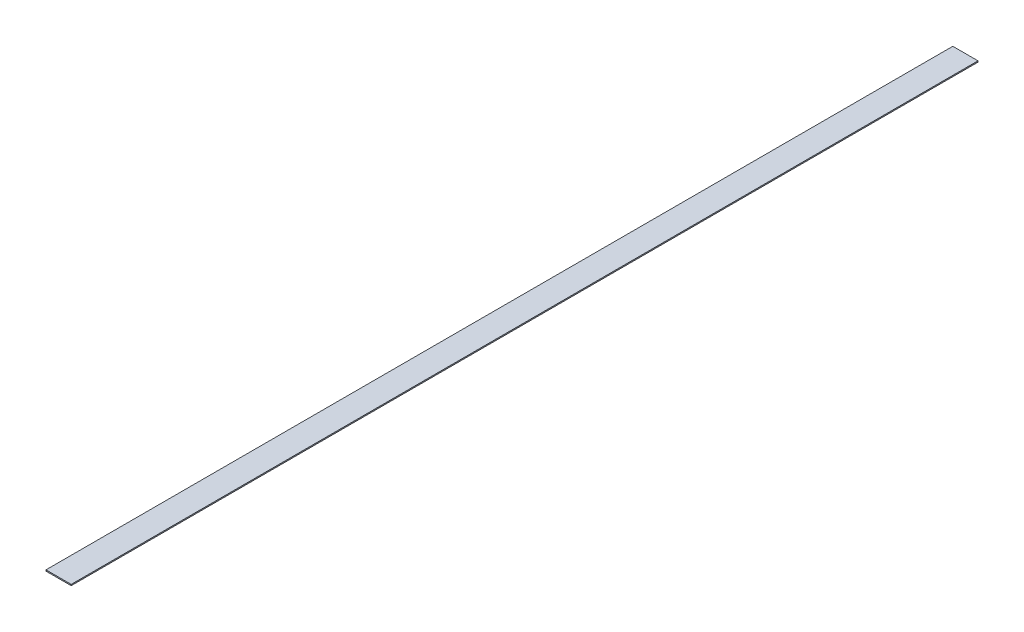
SolidWorks part; units mm, degrees
ref_plane "Front Plane" through (0, 0, 0) normal (0, 0, 1) x (1, 0, 0)
ref_plane "Top Plane" through (0, 0, 0) normal (0, 1, 0) x (1, 0, 0)
ref_plane "Right Plane" through (0, 0, 0) normal (1, 0, 0) x (0, 0, -1)
sketch "Sketch1" plane through (0, 0, 0) normal (0, 0, 1) x (1, 0, 0)
  line L0 (0, 1.1906) -> (0, -1.1906)
  line L1 (-25.4, 0) -> (25.4, 0) construction
  point P6 (0, 0)
  dimension "Width" = 50.8
  dimension "Thk" = 2.3813
sketch "Sketch2" plane through (0, 0, 0) normal (1, 0, 0) x (0, 0, -1)
  line L0 (914.4, 0) -> (-914.4, 0)
  point P4 (0, 0)
  dimension "Length" = 1828.8
sketch "Sketch3" plane through (0, 0, 0) normal (0, 0, 1) x (1, 0, 0)
  line L1 (25.4, 1.1906) -> (-25.4, 1.1906)
  line L2 (25.4, 1.1906) -> (25.4, -1.1906)
  line L3 (25.4, -1.1906) -> (-25.4, -1.1906)
  line L4 (-25.4, 1.1906) -> (-25.4, -1.1906)
  line L5 (25.4, 1.1906) -> (-25.4, -1.1906) construction
  line L6 (25.4, -1.1906) -> (-25.4, 1.1906) construction
  point P0 (0, 0)
extrude "Boss-Extrude1" add sketch "Sketch3" along normal up to vertex (914.4 mm away) and the other way up to vertex (914.4 mm away) up to point (0, 0, 914.4) other way up to point (0, 0, -914.4)
